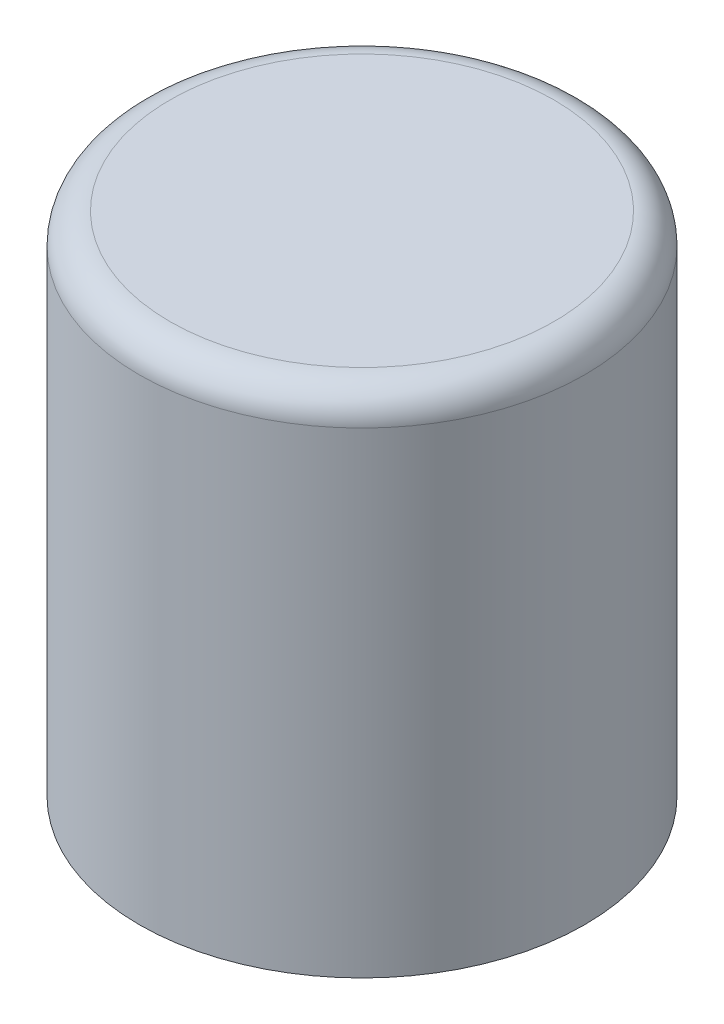
SolidWorks part; units mm, degrees
material "1060 Alloy"
ref_plane "Front Plane" through (0, 0, 0) normal (0, 0, 1) x (1, 0, 0)
ref_plane "Top Plane" through (0, 0, 0) normal (0, 1, 0) x (1, 0, 0)
ref_plane "Right Plane" through (0, 0, 0) normal (1, 0, 0) x (0, 0, -1)
sketch "Sketch1" plane through (0, 0, 0) normal (0, 1, 0) x (1, 0, 0)
  circle A0 centre (0, 0) radius 7.25
  dimension "D1" = 14.5
extrude "Boss-Extrude1" add sketch "Sketch1" along normal blind 16.5
fillet "Fillet1" radius 1 1 edges at (0, 16.5, 7.25)
sketch "Sketch4" plane through (0, 0, 0) normal (0, -1, 0) x (1, 0, 0)
  circle A0 centre (0, 0) radius 3
  dimension "D1" = 6
extrude "Boss-Extrude2" add sketch "Sketch4" along normal blind 1
sketch "Sketch5" plane through (0, -1, 0) normal (0, -1, 0) x (1, 0, 0)
  circle A0 centre (0, 0) radius 0.295
  dimension "D1" = 0.59
extrude "Cut-Extrude2" cut sketch "Sketch5" against normal blind 10
